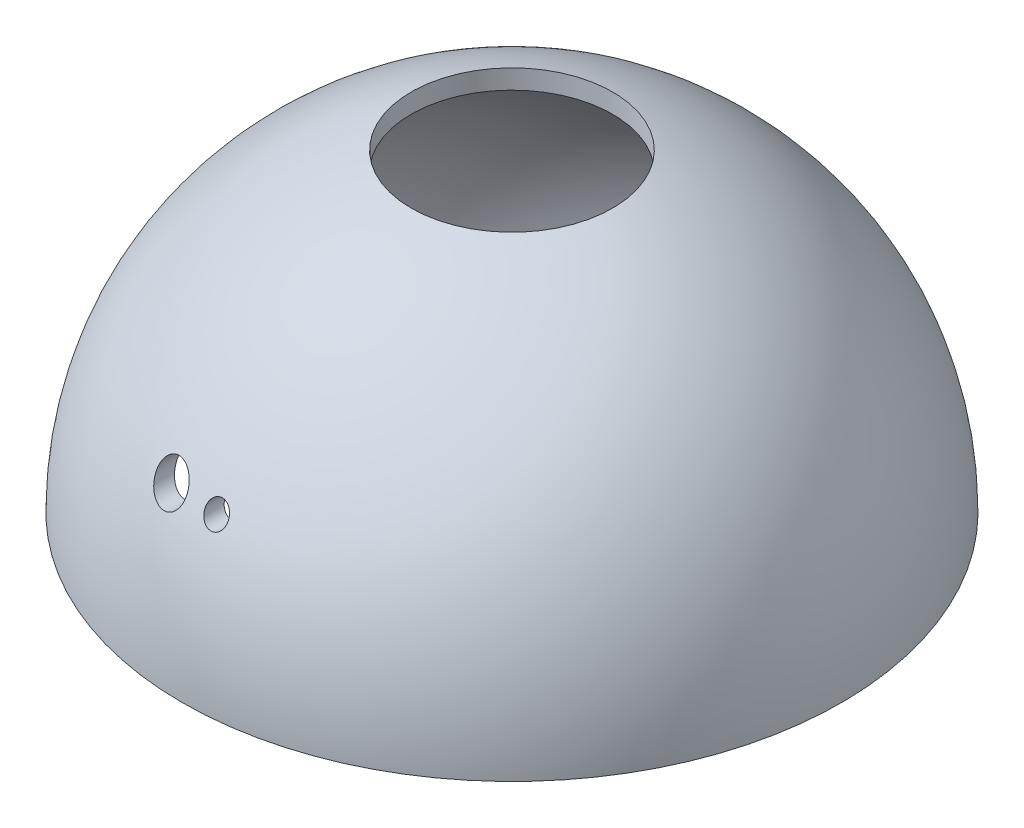
SolidWorks part; units mm, degrees
ref_plane "Front Plane" through (0, 0, 0) normal (0, 0, 1) x (1, 0, 0)
ref_plane "Top Plane" through (0, 0, 0) normal (0, 1, 0) x (1, 0, 0)
ref_plane "Right Plane" through (0, 0, 0) normal (1, 0, 0) x (0, 0, -1)
sketch "Sketch1" plane through (0, 0, 0) normal (0, 0, 1) x (1, 0, 0)
  line L0 (0, 188.6832) -> (0, 0) construction
  line L1 (0, 0) -> (106.4258, 0) construction
  line L2 (85, 0) -> (90, 0)
  line L3 (27.5, 85.6957) -> (27.5, 80.4285)
  arc A0 (90, 0) -> (27.5, 85.6957) centre (0, 0) ccw
  arc A1 (85, 0) -> (27.5, 80.4285) centre (0, 0) ccw
  point P12 (87.5, 0)
  dimension "D3" = 85
  dimension "D1" = 85
  dimension "D2" = 5
  dimension "D4" = 60
revolve "Revolve1" add sketch "Sketch1" angle 360 about L0
sketch "Sketch7" plane through (0, 0, 0) normal (0, 0, 1) x (1, 0, 0)
  circle A1 centre (0, 39.8402) radius 3.15
  circle A2 centre (-13.5798, 39.8402) radius 5
  dimension "D1" = 6.3
  dimension "D2" = 10
extrude "Cut-Extrude5" cut sketch "Sketch7" against normal through all both and the other way through all
